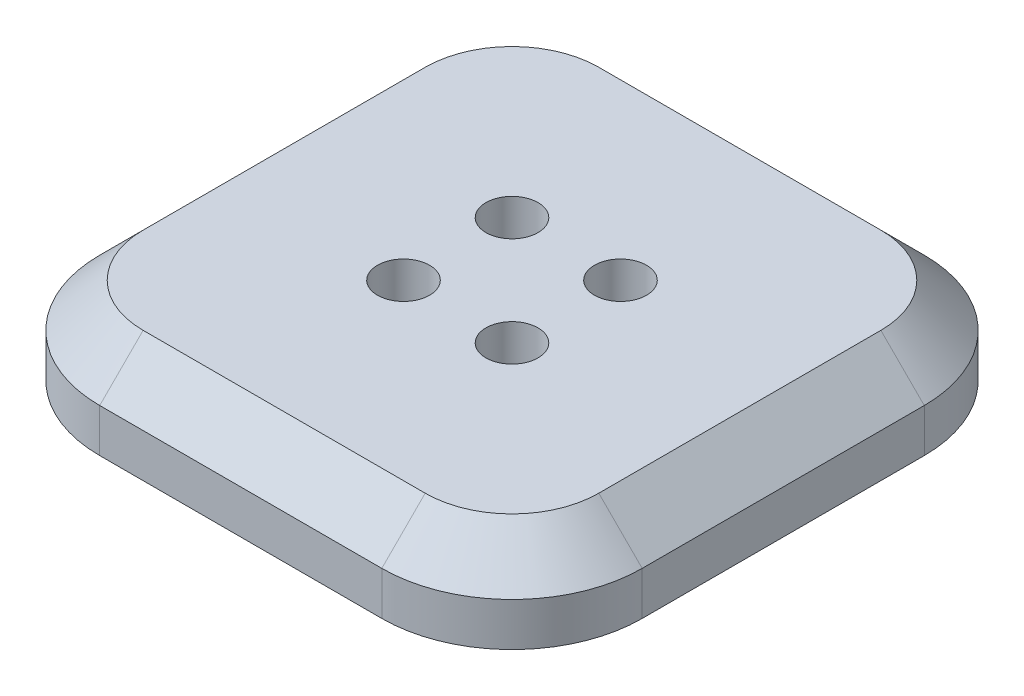
SolidWorks part; units mm, degrees
ref_plane "前基準面" through (0, 0, 0) normal (0, 0, 1) x (1, 0, 0)
ref_plane "上基準面" through (0, 0, 0) normal (0, 1, 0) x (1, 0, 0)
ref_plane "右基準面" through (0, 0, 0) normal (1, 0, 0) x (0, 0, -1)
ref_plane "平面1"
sketch "草圖1" plane through (0, 0, 0) normal (0, 1, 0) x (-1, 0, 0)
  line L0 (62.5, -62.5) -> (-62.5, -62.5)
  line L1 (-62.5, -62.5) -> (-62.5, 62.5)
  line L2 (-62.5, 62.5) -> (62.5, 62.5)
  line L3 (62.5, 62.5) -> (62.5, -62.5)
  dimension "D1" = 125
  dimension "D2" = 125
extrude "擠出1" add sketch "草圖1" along normal blind 20
fillet "圓角1" radius 30 4 edges at (62.5, 10, -62.5) (-62.5, 10, 62.5) (-62.5, 10, -62.5) (62.5, 10, 62.5)
chamfer "倒角1" distance 10 distance2 10 8 edges at (0, 20, 62.5) (53.7132, 20, 53.7132) (62.5, 20, 0) (53.7132, 20, -53.7132) (0, 20, -62.5) (-53.7132, 20, -53.7132) (-62.5, 20, 0) (-53.7132, 20, 53.7132)
hole_wizard "孔1" positions "草圖3" profile "草圖2" legacy
sketch "草圖3" plane through (0, 0, 0) normal (0, -1, 0) x (-1, 0, 0)
  point P1 (-37.5, -37.5)
  point P2 (37.5, -37.5)
  point P3 (37.5, 37.5)
  point P4 (-37.5, 37.5)
sketch "草圖2" plane through (37.5, 0, 37.5) normal (1, 0, 0) x (0, 0, -1)
  line L0 (0, 0) -> (0, 13.6052)
  line L1 (0, 13.6052) -> (6, 10)
  line L2 (6, 10) -> (6, 0)
  line L4 (6, 0) -> (0, 0)
  line L6 (0, 13.6052) -> (-6, 10) construction
  line L7 (0, -4.2442) -> (0, 117.3081) construction
  dimension "直徑" = 12
  dimension "深度" = 10
  dimension "導頭角度" = 118
hole_wizard "孔2" positions "草圖5" profile "草圖4" legacy
sketch "草圖5" plane through (0, 20, 0) normal (0, 1, 0) x (1, 0, 0)
  point P1 (12.5, 12.5)
  point P2 (12.5, -12.5)
  point P3 (-12.5, -12.5)
  point P4 (-12.5, 12.5)
sketch "草圖4" plane through (12.5, 20, -12.5) normal (1, 0, 0) x (0, 0, 1)
  line L0 (0, 0) -> (0, 13.6052)
  line L1 (0, 13.6052) -> (6, 10)
  line L2 (6, 10) -> (6, 0)
  line L4 (6, 0) -> (0, 0)
  line L6 (0, 13.6052) -> (-6, 10) construction
  line L7 (0, -4.2442) -> (0, 117.3081) construction
  dimension "直徑" = 12
  dimension "深度" = 10
  dimension "導頭角度" = 118
